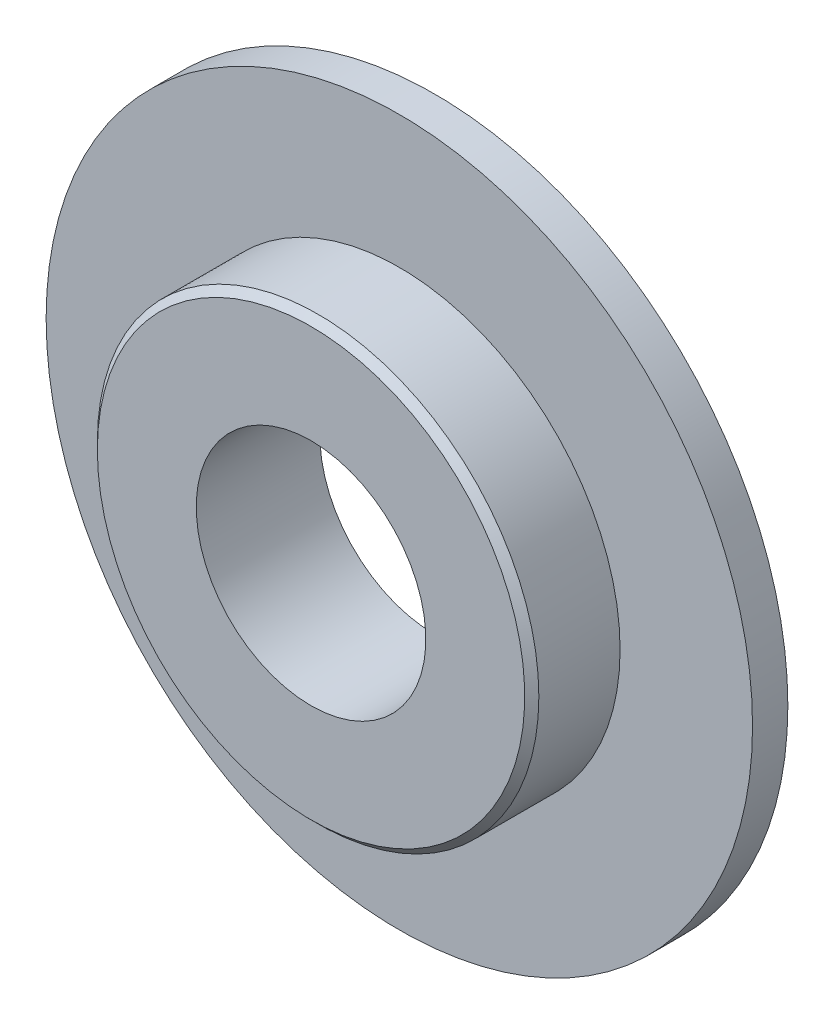
SolidWorks part; units mm, degrees
material "ABS"
ref_plane "Plan de face" through (0, 0, 0) normal (0, 0, 1) x (1, 0, 0)
ref_plane "Plan de dessus" through (0, 0, 0) normal (0, 1, 0) x (1, 0, 0)
ref_plane "Plan de droite" through (0, 0, 0) normal (1, 0, 0) x (0, 0, -1)
sketch "Esquisse1" plane through (38.312, 224.2058, 0) normal (0, 0, -1) x (0.9567, 0.2912, 0)
  circle A0 centre (-101.9349, 203.3355) radius 10
  dimension "D2" = 20
extrude "Boss.-Extru.1" add sketch "Esquisse1" along normal blind 1
sketch "Esquisse2" plane through (0, 0, 0) normal (0, 0, 1) x (1, 0, 0)
  circle A0 centre (0, 0) radius 6.25
  dimension "D1" = 12.5
extrude "Boss.-Extru.2" add sketch "Esquisse2" along normal blind 2.5
sketch "Esquisse3" plane through (0, 0, -1) normal (0, 0, -1) x (1, 0, 0)
  circle A0 centre (0, 0) radius 3.25
  dimension "D1" = 6.5
extrude "Enlèv. mat.-Extru.1" cut sketch "Esquisse3" against normal through all
chamfer "Chanfrein1" distance 0.2 angle 45 1 edges at (6.25, 0, 2.5)
